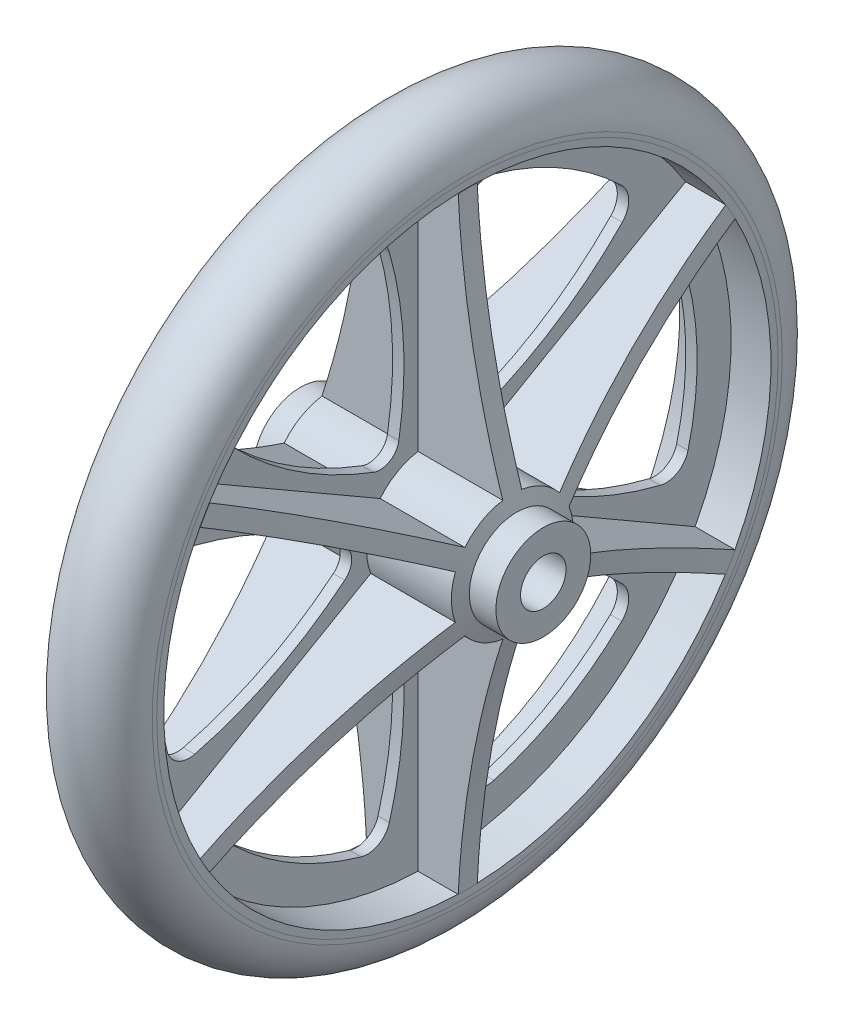
SolidWorks part; units mm, degrees
ref_plane "Alzado" through (0, 0, 0) normal (0, 0, 1) x (1, 0, 0)
ref_plane "Planta" through (0, 0, 0) normal (0, 1, 0) x (1, 0, 0)
ref_plane "Vista lateral" through (0, 0, 0) normal (1, 0, 0) x (0, 0, -1)
sketch "Croquis1" plane through (0, 0, 0) normal (0, 0, 1) x (1, 0, 0)
  line L0 (0, 0) -> (-207.4481, 0) construction
  line L3 (12, 80) -> (-12, 80)
  line L4 (-12, 82) -> (-12, 80)
  line L6 (12, 82) -> (12, 80)
  arc A3 (12, 82) -> (-12, 82) centre (0, 82) ccw
  dimension "D1" = 24
  dimension "D2" = 2
  dimension "D3" = 80
revolve "Revolución1" add sketch "Croquis1" angle 360 about L0
sketch "Croquis9" plane through (0, 0, 0) normal (1, 0, 0) x (0, 0, -1)
  circle A0 centre (0, 0) radius 16
  circle A1 centre (0, 0) radius 6
  dimension "D1" = 32
  dimension "D2" = 12
extrude "Saliente-Extruir8" add sketch "Croquis9" along normal blind 32 and the other way blind 32 separate body
sketch "Croquis10" plane through (32, 0, 0) normal (1, 0, 0) x (0, 0, -1)
  circle A0 centre (0, 0) radius 12.5
  circle A1 centre (0, 0) radius 16
  dimension "D1" = 25
extrude "Cortar-Extruir1" cut sketch "Croquis10" against normal blind 9
sketch "Croquis11" plane through (-32, 0, 0) normal (-1, 0, 0) x (0, 0, 1)
  circle A1 centre (0, 0) radius 12.5
  circle A2 centre (0, 0) radius 16
  dimension "D1" = 25
extrude "Cortar-Extruir2" cut sketch "Croquis11" against normal blind 9
sketch "Croquis12" plane through (0, 0, 0) normal (1, 0, 0) x (0, 0, -1)
  line L0 (67.9982, 42.1455) -> (12.476, 10.0898)
  line L1 (70.4982, 37.8154) -> (14.976, 5.7597)
  line L3 (-2.5, 79.9609) -> (-2.5, 15.8494)
  line L5 (2.5, 79.9609) -> (2.5, 15.8494)
  line L6 (70.4982, -37.8154) -> (14.976, -5.7597)
  line L7 (67.9982, -42.1455) -> (12.476, -10.0898)
  line L8 (2.5, -79.9609) -> (2.5, -15.8494)
  line L9 (-2.5, -79.9609) -> (-2.5, -15.8494)
  line L10 (-67.9982, -42.1455) -> (-12.476, -10.0898)
  line L11 (-70.4982, -37.8154) -> (-14.976, -5.7597)
  line L12 (-70.4982, 37.8154) -> (-14.976, 5.7597)
  line L13 (-67.9982, 42.1455) -> (-12.476, 10.0898)
  circle A1 centre (0, 0) radius 16.0454
  circle A3 centre (0, 0) radius 80
  circle A4 centre (0, 0) radius 16.0454
  circle A6 centre (0, 0) radius 16.0454
  circle A8 centre (0, 0) radius 16.0454
  circle A10 centre (0, 0) radius 16.0454
  circle A12 centre (0, 0) radius 16.0454
  circle A13 centre (0, 0) radius 16.0454
  point P35 (0, 0)
  dimension "D3" = 32.0908
  dimension "D1" = 5
  dimension "D2" = 6
extrude "Saliente-Extruir9" add sketch "Croquis12" along normal blind 25 contours L3 A3 L13 A1 | L0 A3 L5 A1 | L6 A3 L1 A1 | L8 A3 L7 A1 | L10 A3 L9 A1 | L12 A3 L11 A1
sketch "Croquis15" plane through (0, 0, 0.6699) normal (0, -1, 0) x (1, 0, 0)
  line L0 (36.3178, -0.6699) -> (-36.4294, -0.6699) construction
  line L3 (25, -68.6681) -> (12, -68.6681)
  line L5 (25, -13.1699) -> (11.9563, -13.1699)
  line L6 (25, -13.1699) -> (25, -83.6925)
  line L7 (25, -83.6925) -> (11.9563, -83.6925)
  line L8 (11.9563, -13.1699) -> (11.9563, -83.6925)
  arc A0 (-12, -82.6699) -> (12, -82.6699) centre (0, -82.6699) ccw construction
  arc A1 (11.9563, -83.6925) -> (25, -13.1699) centre (256.3825, -92.4333) cw
revolve "Cortar-Revolución3" cut sketch "Croquis15" angle 360 about L0
sketch "Croquis18" plane through (0, 0, 0) normal (1, 0, 0) x (0, 0, -1)
  circle A0 centre (0, 0) radius 80
extrude "Saliente-Extruir10" add sketch "Croquis18" along normal blind 1.5
sketch "Croquis19" plane through (1.5, 0, 0) normal (1, 0, 0) x (0, 0, -1)
  line L0 (0, 0) -> (48.8128, 84.5463) construction
  line L1 (67.9982, 42.1455) -> (12.476, 10.0898) construction
  line L2 (2.5, 79.9609) -> (2.5, 15.8494) construction
  arc A0 (7.5669, 20.8352) -> (14.2603, 16.9707) centre (12.5, 21.6506) ccw
  arc A1 (10.0529, 65.0467) -> (7.5669, 20.8352) centre (107.6657, 37.3824) ccw
  arc A2 (17.4715, 69.1805) -> (10.0529, 65.0467) centre (15.8256, 63.4107) ccw
  arc A3 (12.476, 10.0898) -> (2.5, 15.8494) centre (0, 0) ccw construction
  arc A4 (51.1763, 49.721) -> (17.4715, 69.1805) centre (-4.4747, -7.7504) ccw
  arc A5 (51.1763, 49.721) -> (51.3056, 41.2294) centre (47.0025, 45.4107) cw
  arc A6 (51.3056, 41.2294) -> (14.2603, 16.9707) centre (-21.4588, 111.9325) cw
  arc A7 (68.6478, -19.4595) -> (68.6478, 19.4595) centre (-8.9494, 0) ccw
  arc A8 (68.6478, 19.4595) -> (61.3585, 23.8173) centre (62.828, 18) ccw
  arc A9 (61.3585, 23.8173) -> (21.8273, 3.8644) centre (86.207, -74.5501) ccw
  arc A10 (21.8273, 3.8644) -> (21.8273, -3.8644) centre (25, 0) ccw
  arc A11 (61.3585, -23.8173) -> (21.8273, -3.8644) centre (86.207, 74.5501) cw
  arc A12 (68.6478, -19.4595) -> (61.3585, -23.8173) centre (62.828, -18) cw
  arc A13 (17.4715, -69.1805) -> (51.1763, -49.721) centre (-4.4747, 7.7504) ccw
  arc A14 (51.1763, -49.721) -> (51.3056, -41.2294) centre (47.0025, -45.4107) ccw
  arc A15 (51.3056, -41.2294) -> (14.2603, -16.9707) centre (-21.4588, -111.9325) ccw
  arc A16 (14.2603, -16.9707) -> (7.5669, -20.8352) centre (12.5, -21.6506) ccw
  arc A17 (10.0529, -65.0467) -> (7.5669, -20.8352) centre (107.6657, -37.3824) cw
  arc A18 (17.4715, -69.1805) -> (10.0529, -65.0467) centre (15.8256, -63.4107) cw
  arc A19 (-51.1763, -49.721) -> (-17.4715, -69.1805) centre (4.4747, 7.7504) ccw
  arc A20 (-17.4715, -69.1805) -> (-10.0529, -65.0467) centre (-15.8256, -63.4107) ccw
  arc A21 (-10.0529, -65.0467) -> (-7.5669, -20.8352) centre (-107.6657, -37.3824) ccw
  arc A22 (-7.5669, -20.8352) -> (-14.2603, -16.9707) centre (-12.5, -21.6506) ccw
  arc A23 (-51.3056, -41.2294) -> (-14.2603, -16.9707) centre (21.4588, -111.9325) cw
  arc A24 (-51.1763, -49.721) -> (-51.3056, -41.2294) centre (-47.0025, -45.4107) cw
  arc A25 (-68.6478, 19.4595) -> (-68.6478, -19.4595) centre (8.9494, 0) ccw
  arc A26 (-68.6478, -19.4595) -> (-61.3585, -23.8173) centre (-62.828, -18) ccw
  arc A27 (-61.3585, -23.8173) -> (-21.8273, -3.8644) centre (-86.207, 74.5501) ccw
  arc A28 (-21.8273, -3.8644) -> (-21.8273, 3.8644) centre (-25, 0) ccw
  arc A29 (-61.3585, 23.8173) -> (-21.8273, 3.8644) centre (-86.207, -74.5501) cw
  arc A30 (-68.6478, 19.4595) -> (-61.3585, 23.8173) centre (-62.828, 18) cw
  arc A31 (-17.4715, 69.1805) -> (-51.1763, 49.721) centre (4.4747, -7.7504) ccw
  arc A32 (-51.1763, 49.721) -> (-51.3056, 41.2294) centre (-47.0025, 45.4107) ccw
  arc A33 (-51.3056, 41.2294) -> (-14.2603, 16.9707) centre (21.4588, 111.9325) ccw
  arc A34 (-14.2603, 16.9707) -> (-7.5669, 20.8352) centre (-12.5, 21.6506) ccw
  arc A35 (-10.0529, 65.0467) -> (-7.5669, 20.8352) centre (-107.6657, 37.3824) cw
  arc A36 (-17.4715, 69.1805) -> (-10.0529, 65.0467) centre (-15.8256, 63.4107) cw
  point P85 (0, 0)
  dimension "D2" = 10
  dimension "D3" = 12
  dimension "D5" = 18
  dimension "D6" = 13.3256
  dimension "D7" = 80
  dimension "D8" = 101.4573
  dimension "D1" = 30
  dimension "D4" = 25
  dimension "D9" = 6
extrude "Cortar-Extruir6" cut sketch "Croquis19" against normal blind 1.5
sketch "Croquis17" plane through (0, 0, 0) normal (0, 0, 1) x (1, 0, 0)
  line L1 (0, 103.7808) -> (-44.7921, 103.7808)
  line L2 (0, 103.7808) -> (0, -102.7095)
  line L3 (0, -102.7095) -> (-44.7921, -102.7095)
  line L4 (-44.7921, 103.7808) -> (-44.7921, -102.7095)
extrude "Cortar-Extruir5" cut sketch "Croquis17" against normal blind 106 and the other way blind 100
mirror "Simetría1" about plane through (0, 0, 0) normal (1, 0, 0) of bodies 116
sketch "Croquis20" plane through (25, 0, 0) normal (1, 0, 0) x (0, 0, -1)
  circle A0 centre (0, 0) radius 6
extrude "Cortar-Extruir7" cut sketch "Croquis20" against normal blind 80
